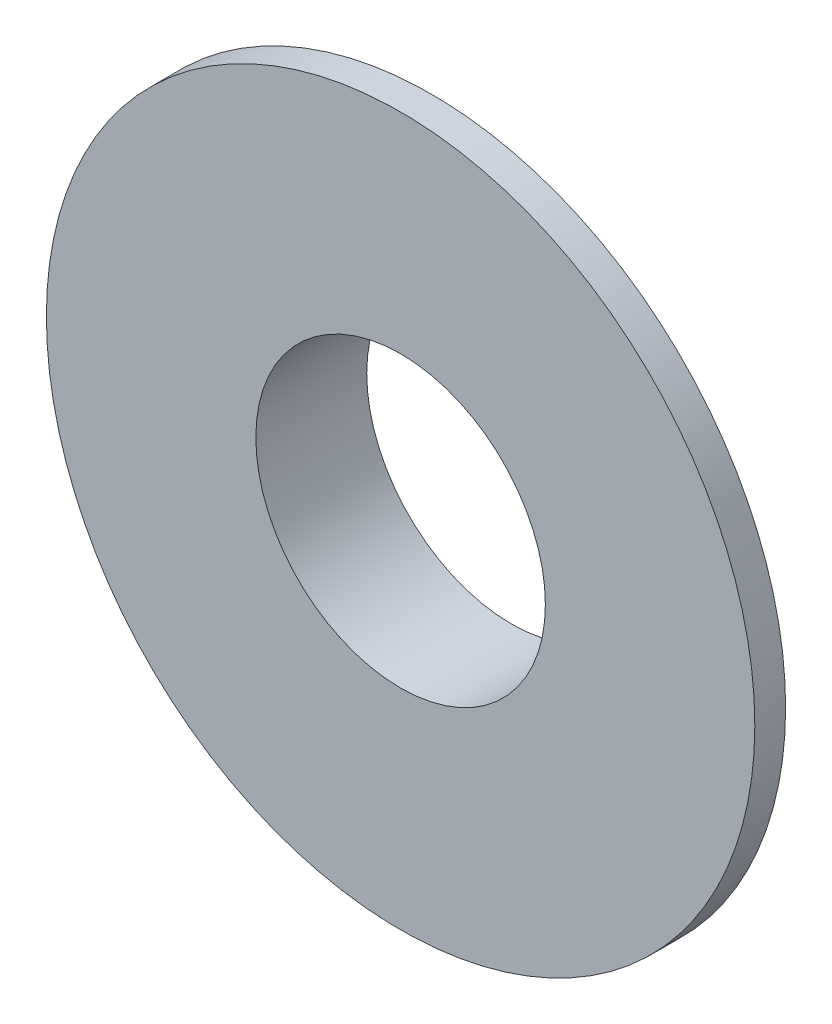
SolidWorks part; units mm, degrees
ref_plane "Front Plane" through (0, 0, 0) normal (0, 0, 1) x (1, 0, 0)
ref_plane "Top Plane" through (0, 0, 0) normal (0, 1, 0) x (1, 0, 0)
ref_plane "Right Plane" through (0, 0, 0) normal (1, 0, 0) x (0, 0, -1)
sketch "Sketch1" plane through (0, 0, 0) normal (1, 0, 0) x (0, 0, -1)
  line L0 (-18, 57.5) -> (-13, 57.5)
  line L1 (-13, 57.5) -> (-13, 29.25)
  line L2 (-13, 29.25) -> (0, 29.25)
  line L3 (0, 29.25) -> (0, 23.5)
  line L4 (0, 23.5) -> (-18, 23.5)
  line L5 (-18, 23.5) -> (-18, 57.5)
  line L6 (0, 0) -> (-84.7011, 0) construction
  dimension "D1" = 47
  dimension "D2" = 58.5
  dimension "D3" = 5
  dimension "D4" = 13
  dimension "Housing OD" = 115
revolve "Revolve1" add sketch "Sketch1" angle 360 about L6
equation "\"D1@Sketch1\" = \"Bearing OD@Motor Bearing<1>.Part\""
